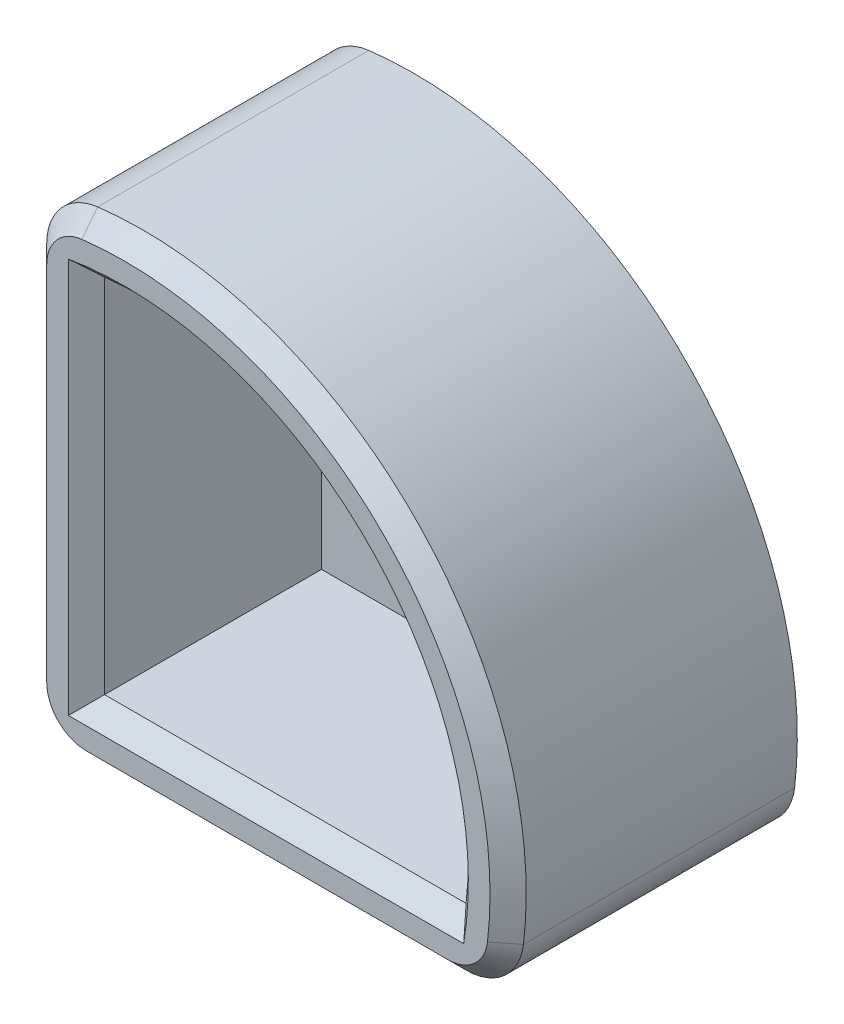
SolidWorks part; units mm, degrees
ref_plane "前视基准面" through (0, 0, 0) normal (0, 0, 1) x (1, 0, 0)
ref_plane "上视基准面" through (0, 0, 0) normal (0, 1, 0) x (1, 0, 0)
ref_plane "右视基准面" through (0, 0, 0) normal (1, 0, 0) x (0, 0, -1)
sketch "草图1" plane through (0, 0, 0) normal (0, 0, 1) x (1, 0, 0)
  line L0 (0, 0) -> (10, 0) construction
  line L1 (0, 0) -> (0, 10) construction
  line L2 (-1.6, -1.6) -> (11.323, -1.6)
  line L3 (-1.6, -1.6) -> (-1.6, 11.323)
  arc A0 (0, 10) -> (10, 0) centre (1.063, 1.063) cw construction
  arc A1 (-1.6, 11.323) -> (11.323, -1.6) centre (1.063, 1.063) cw
  dimension "D1" = 10
  dimension "D3" = 9
  dimension "D2" = 10
  dimension "D4" = 1.6
extrude "凸台-拉伸1" add sketch "草图1" along normal blind 8
sketch "草图2" plane through (0, 0, 8) normal (0, 0, 1) x (1, 0, 0)
  line L0 (0, 0) -> (10, 0)
  line L1 (0, 0) -> (0, 10)
  arc A0 (0, 10) -> (10, 0) centre (1.063, 1.063) cw
  dimension "D1" = 10
  dimension "D3" = 9
  dimension "D2" = 10
extrude "切除-拉伸1" cut sketch "草图2" against normal blind 6.5
sketch "草图5" plane through (0, 0, 1.5) normal (0, 0, 1) x (1, 0, 0)
  line L3 (2.6161, 4.6161) -> (4.6161, 2.6161)
  line L4 (4.3839, 6.3839) -> (6.3839, 4.3839)
  line L6 (0, 10) -> (0, 0) construction
  arc A0 (4.3839, 6.3839) -> (2.6161, 4.6161) centre (3.5, 5.5) ccw
  arc A1 (4.6161, 2.6161) -> (6.3839, 4.3839) centre (5.5, 3.5) ccw
  point P4 (0, 0)
  dimension "D1" = 2.5
  dimension "D2" = 2.5
  dimension "D5" = 3.5
  dimension "D3" = 2
  dimension "D4" = 2
  dimension "D6" = 5.5
extrude "切除-拉伸2" cut sketch "草图5" against normal through all
fillet "圆角1" radius 1.6 3 edges at (-1.6, 11.323, 4) (-1.6, -1.6, 4) (11.323, -1.6, 4)
chamfer "倒角2" distance 0.5 angle 45 9 edges at (8.5583, 8.5583, 8) (5, -1.6, 8) (-1.6, 5, 8) (7.427, 7.427, 8) (0, 5, 8) (5, 0, 8) (11.0625, -1.1963, 8) (-1.1314, -1.1314, 8) (-1.1963, 11.0625, 8)
